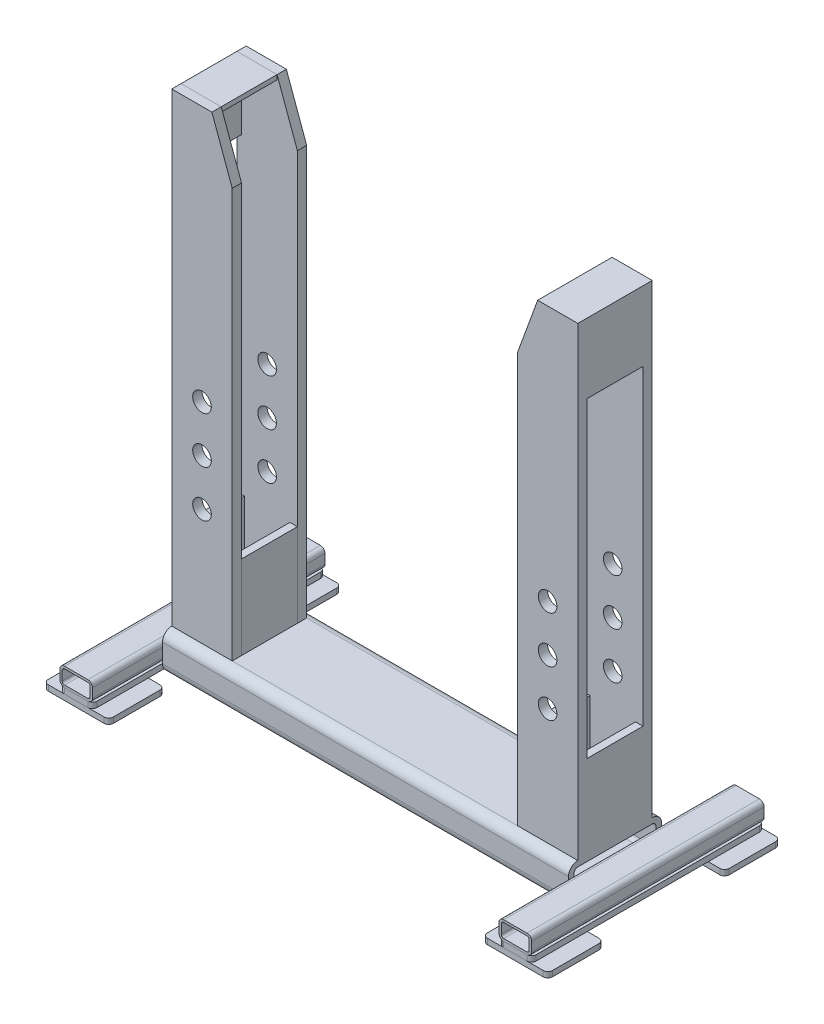
SolidWorks part; units mm, degrees
other "DetailItem8"
other "DetailItem9"
other "DetailItem10"
other "DetailItem11"
other "DetailItem12"
other "DetailItem13"
other "DetailItem14"
other "DetailItem15"
other "DetailItem16"
other "DetailItem17"
other "DetailItem18"
other "DetailItem19"
other "DetailItem20"
other "Weld Folder"
other "Weld Bead4"
other "Weld Bead5"
other "Weld Bead6"
other "Weld Bead7"
other "Weld Bead8"
other "Weld Bead9"
other "Weld Bead10"
other "Weld Bead11"
other "Weld Bead12"
other "Weld Bead13"
other "Weld Bead14"
other "Weld Bead15"
other "Weld Bead16"
ref_plane "Front Plane" through (0, 0, 0) normal (0, 0, 1) x (1, 0, 0)
ref_plane "Top Plane" through (0, 0, 0) normal (0, 1, 0) x (1, 0, 0)
ref_plane "Right Plane" through (0, 0, 0) normal (1, 0, 0) x (0, 0, -1)
sketch "Sketch1" plane through (0, 0, 0) normal (0, 1, 0) x (1, 0, 0)
  line L0 (0, 245.528) -> (0, 0)
  line L1 (0, 0) -> (285.8385, 0)
  line L2 (-472, 250) -> (-472, -250)
  line L3 (472, 250) -> (472, -250)
  line L5 (-497, -250) -> (-447, -250)
  line L6 (-507, -240) -> (-507, 240)
  line L7 (-497, 250) -> (-447, 250)
  line L8 (-437, -240) -> (-437, 240)
  line L9 (-507, -250) -> (-437, 250) construction
  line L10 (-507, 250) -> (-437, -250) construction
  line L11 (447, -250) -> (497, -250)
  line L12 (437, -240) -> (437, 240)
  line L13 (447, 250) -> (497, 250)
  line L14 (507, -240) -> (507, 240)
  line L15 (437, -250) -> (507, 250) construction
  line L16 (437, 250) -> (507, -250) construction
  arc A0 (497, 250) -> (507, 240) centre (497, 240) cw
  arc A1 (437, 240) -> (447, 250) centre (447, 240) cw
  arc A2 (447, -250) -> (437, -240) centre (447, -240) cw
  arc A3 (497, -250) -> (507, -240) centre (497, -240) ccw
  arc A4 (-497, -250) -> (-507, -240) centre (-497, -240) cw
  arc A5 (-447, -250) -> (-437, -240) centre (-447, -240) ccw
  arc A6 (-447, 250) -> (-437, 240) centre (-447, 240) cw
  arc A7 (-507, 240) -> (-497, 250) centre (-497, 240) cw
  point P8 (-472, 0)
  point P13 (472, 0)
  dimension "D10" = 10
  dimension "D1" = 472
  dimension "D2" = 472
  dimension "D3" = 250
  dimension "D4" = 500
  dimension "D5" = 250
  dimension "D6" = 70
  dimension "D7" = 500
  dimension "D8" = 500
  dimension "D9" = 70
extrude "Boss-Extrude1" add sketch "Sketch1" along normal blind 12 contours L5 A5 L8 A6 L7 A7 L6 A4 | L14 A0 L13 A1 L12 A2 L11 A3
ref_plane "Plane1" through (0, 32, 0) normal (0, 1, 0) x (1, 0, 0)
sketch "Sketch2" plane through (0, 32, 0) normal (0, 1, 0) x (1, 0, 0)
  line L0 (-472, 250) -> (-472, -250)
  line L1 (-497, 250) -> (-447, 250) construction
  line L2 (-497, -250) -> (-447, -250) construction
  line L3 (472, -250) -> (472, 250)
  line L4 (447, -250) -> (497, -250) construction
  line L5 (447, 250) -> (497, 250) construction
other "Rectangular tube 70 X 40 X 5(1)"
ref_plane "Plane2" through (472, 32, 250) normal (0, 0, -1) x (0, 1, 0)
sketch "Sketch11" plane through (472, 32, 250) normal (0, 0, -1) x (0, 1, 0)
  line L0 (-10, -30) -> (10, -30)
  line L1 (-15, -25) -> (-15, 25)
  line L2 (10, 30) -> (-10, 30)
  line L3 (15, 25) -> (15, -25)
  line L4 (-10, -35) -> (10, -35)
  line L5 (-20, -25) -> (-20, 25)
  line L6 (10, 35) -> (-10, 35)
  line L7 (20, 25) -> (20, -25)
  arc A0 (20, 25) -> (10, 35) centre (10, 25) ccw
  arc A1 (10, -35) -> (20, -25) centre (10, -25) ccw
  arc A2 (-20, -25) -> (-10, -35) centre (-10, -25) ccw
  arc A3 (-10, 35) -> (-20, 25) centre (-10, 25) ccw
  arc A4 (-10, 30) -> (-15, 25) centre (-10, 25) ccw
  arc A5 (15, 25) -> (10, 30) centre (10, 25) ccw
  arc A6 (10, -30) -> (15, -25) centre (10, -25) ccw
  arc A7 (-15, -25) -> (-10, -30) centre (-10, -25) ccw
  point P0 (0, 35)
  point P1 (20, 0)
  point P2 (0, -35)
  point P3 (-20, 0)
  point P4 (-20, 35)
  point P5 (20, 35)
  point P6 (20, -35)
  point P7 (-20, -35)
  point P8 (0, 0)
  point P33 (0, 0)
  dimension "D1" = 10
  dimension "Thickness" = 5
  dimension "V_leg" = 70
  dimension "H_leg" = 40
sketch "Sketch15" plane through (0, 0, 0) normal (0, 0, 1) x (1, 0, 0)
  line L0 (-436.5, 32) -> (436.5, 32)
  line L1 (0, 0) -> (0, 69.2189) construction
  line L2 (447, 52) -> (497, 52) construction
  dimension "D1" = 436.5
  dimension "D2" = 873
  dimension "D3" = 20
other "Rectangular tube 120 X 80 X 8(1)"
ref_plane "Plane3" through (-436.5, 32, 0) normal (1, 0, 0) x (0, 1, 0)
sketch "Sketch12" plane through (-436.5, 32, 0) normal (1, 0, 0) x (0, 1, 0)
  line L0 (-20, -88) -> (20, -88)
  line L1 (-28, -80) -> (-28, 80)
  line L2 (20, 88) -> (-20, 88)
  line L3 (28, 80) -> (28, -80)
  line L4 (-20, -100) -> (20, -100)
  line L5 (-40, -80) -> (-40, 80)
  line L6 (20, 100) -> (-20, 100)
  line L7 (40, 80) -> (40, -80)
  arc A0 (40, 80) -> (20, 100) centre (20, 80) ccw
  arc A1 (20, -100) -> (40, -80) centre (20, -80) ccw
  arc A2 (-40, -80) -> (-20, -100) centre (-20, -80) ccw
  arc A3 (-20, 100) -> (-40, 80) centre (-20, 80) ccw
  arc A4 (-20, 88) -> (-28, 80) centre (-20, 80) ccw
  arc A5 (28, 80) -> (20, 88) centre (20, 80) ccw
  arc A6 (20, -88) -> (28, -80) centre (20, -80) ccw
  arc A7 (-28, -80) -> (-20, -88) centre (-20, -80) ccw
  point P0 (0, 100)
  point P1 (40, 0)
  point P2 (0, -100)
  point P3 (-40, 0)
  point P4 (-40, 100)
  point P5 (40, 100)
  point P6 (40, -100)
  point P7 (-40, -100)
  point P8 (0, 0)
  point P33 (0, 0)
  dimension "D1" = 20
  dimension "Thickness" = 12
  dimension "V_leg" = 200
  dimension "H_leg" = 80
sketch "Sketch17" plane through (0, 0, 0) normal (0, -1, 0) x (1, 0, 0)
  line L0 (437, 240) -> (437, -240) construction
  line L1 (412, 250) -> (532, 250)
  line L2 (402, 240) -> (402, 140)
  line L3 (412, 130) -> (532, 130)
  line L4 (542, 240) -> (542, 140)
  line L5 (507, 240) -> (507, -240) construction
  line L6 (447, 250) -> (497, 250) construction
  line L7 (0, 197.9087) -> (0, 0) construction
  line L8 (0, 0) -> (116.6037, 0) construction
  line L9 (-436.5, 0) -> (436.5, 0) construction
  line L10 (-542, 240) -> (-542, 140)
  line L11 (-412, 130) -> (-532, 130)
  line L12 (-402, 240) -> (-402, 140)
  line L13 (-412, 250) -> (-532, 250)
  line L14 (542, -240) -> (542, -140)
  line L15 (412, -130) -> (532, -130)
  line L16 (402, -240) -> (402, -140)
  line L17 (412, -250) -> (532, -250)
  line L18 (-412, -250) -> (-532, -250)
  line L19 (-402, -240) -> (-402, -140)
  line L20 (-412, -130) -> (-532, -130)
  line L21 (-542, -240) -> (-542, -140)
  arc A0 (532, 250) -> (542, 240) centre (532, 240) cw
  arc A1 (532, 130) -> (542, 140) centre (532, 140) ccw
  arc A2 (402, 140) -> (412, 130) centre (412, 140) ccw
  arc A3 (412, 250) -> (402, 240) centre (412, 240) ccw
  arc A12 (-412, 250) -> (-402, 240) centre (-412, 240) cw
  arc A13 (-402, 140) -> (-412, 130) centre (-412, 140) cw
  arc A14 (-532, 130) -> (-542, 140) centre (-532, 140) cw
  arc A15 (-532, 250) -> (-542, 240) centre (-532, 240) ccw
  arc A20 (412, -250) -> (402, -240) centre (412, -240) cw
  arc A21 (402, -140) -> (412, -130) centre (412, -140) cw
  arc A22 (532, -130) -> (542, -140) centre (532, -140) cw
  arc A23 (532, -250) -> (542, -240) centre (532, -240) ccw
  arc A24 (-532, -250) -> (-542, -240) centre (-532, -240) cw
  arc A25 (-532, -130) -> (-542, -140) centre (-532, -140) ccw
  arc A26 (-402, -140) -> (-412, -130) centre (-412, -140) ccw
  arc A27 (-412, -250) -> (-402, -240) centre (-412, -240) ccw
  point P12 (542, 250)
  point P15 (542, 130)
  point P54 (-542, 130)
  point P55 (-542, 250)
  point P76 (542, -130)
  point P77 (542, -250)
  point P98 (-542, -250)
  point P99 (-542, -130)
  dimension "D4" = 10
  dimension "D1" = 120
  dimension "D2" = 35
  dimension "D3" = 35
extrude "Boss-Extrude2" add sketch "Sketch17" along normal blind 12 separate body
sketch "Sketch18" plane through (0, 72, 0) normal (0, 1, 0) x (1, 0, 0)
  line L1 (-436.5, -80) -> (-306.5, -80)
  line L2 (-436.5, -80) -> (-436.5, -60)
  line L3 (-436.5, -60) -> (-306.5, -60)
  line L4 (-306.5, -80) -> (-306.5, -60)
  line L5 (-436.5, 80) -> (-306.5, 80)
  line L6 (-436.5, 80) -> (-436.5, 60)
  line L7 (-436.5, 60) -> (-306.5, 60)
  line L8 (-306.5, 80) -> (-306.5, 60)
  dimension "D1" = 130
  dimension "D2" = 20
  dimension "D3" = 130
  dimension "D4" = 20
extrude "Boss-Extrude3" add sketch "Sketch18" along normal blind 1000 separate body
sketch "Sketch19" plane through (0, 0, -60) normal (0, 0, 1) x (1, 0, 0)
  line L1 (-436.5, 72) -> (-420.5, 72)
  line L2 (-436.5, 72) -> (-436.5, 252)
  line L3 (-436.5, 252) -> (-420.5, 252)
  line L4 (-420.5, 72) -> (-420.5, 252)
  line L5 (-306.5, 72) -> (-322.5, 72)
  line L6 (-306.5, 72) -> (-306.5, 252)
  line L7 (-306.5, 252) -> (-322.5, 252)
  line L8 (-322.5, 72) -> (-322.5, 252)
  dimension "D1" = 180
  dimension "D2" = 180
  dimension "D3" = 16
  dimension "D4" = 16
extrude "Boss-Extrude4" add sketch "Sketch19" along normal up to next (120 mm away) separate body
mirror "Mirror1" about plane through (0, 0, 0) normal (1, 0, 0) of "Boss-Extrude3", "Boss-Extrude4"
sketch "Sketch20" plane through (0, 0, 80) normal (0, 0, 1) x (1, 0, 0)
  line L0 (-306.5, 1072) -> (-350.1764, 1072)
  line L1 (-436.5, 1072) -> (-306.5, 1072) construction
  line L2 (-350.1764, 1072) -> (-306.5, 952)
  line L3 (-306.5, 1072) -> (-306.5, 72) construction
  line L4 (-306.5, 952) -> (-306.5, 1072)
  line L5 (306.5, 1072) -> (306.5, 952)
  line L6 (306.5, 1072) -> (306.5, 72) construction
  line L7 (306.5, 952) -> (350.1764, 1072)
  line L8 (350.1764, 1072) -> (306.5, 1072)
  dimension "D1" = 20
  dimension "D2" = 120
  dimension "D3" = 20
  dimension "D4" = 120
extrude "Cut-Extrude1" cut sketch "Sketch20" against normal blind 1200
sketch "Sketch21" plane through (0, 0, 80) normal (0, 0, 1) x (1, 0, 0)
  line L0 (-436.5, 1072) -> (-436.5, 72) construction
  line L1 (-436.5, 72) -> (-306.5, 72) construction
  circle A0 centre (-371.5, 322) radius 20
  dimension "D1" = 40
  dimension "D2" = 65
  dimension "D3" = 250
extrude "Cut-Extrude2" cut sketch "Sketch21" against normal blind 1200
pattern_linear "LPattern1" count 3 spacing 100 along (0, 1, 0) of "Cut-Extrude2"
mirror "Mirror2" about plane through (0, 0, 0) normal (1, 0, 0) of "LPattern1", "Cut-Extrude2"
sketch "Sketch22" plane through (0, 0, -60) normal (0, 0, 1) x (1, 0, 0)
  line L0 (-436.5, 1072) -> (-350.1764, 1072)
  line L1 (-350.1764, 1072) -> (-350.1764, 1062)
  line L2 (-350.1764, 1062) -> (-426.5, 1062)
  line L3 (-426.5, 1062) -> (-426.5, 922)
  line L4 (-426.5, 922) -> (-436.5, 922)
  line L5 (-436.5, 1072) -> (-436.5, 72) construction
  line L6 (-436.5, 922) -> (-436.5, 1072)
  dimension "D1" = 10
  dimension "D2" = 150
  dimension "D3" = 10
extrude "Boss-Extrude5" add sketch "Sketch22" along normal up to next (120 mm away) separate body
mirror "Mirror5" about plane through (0, 0, 0) normal (1, 0, 0) of "Boss-Extrude5"
